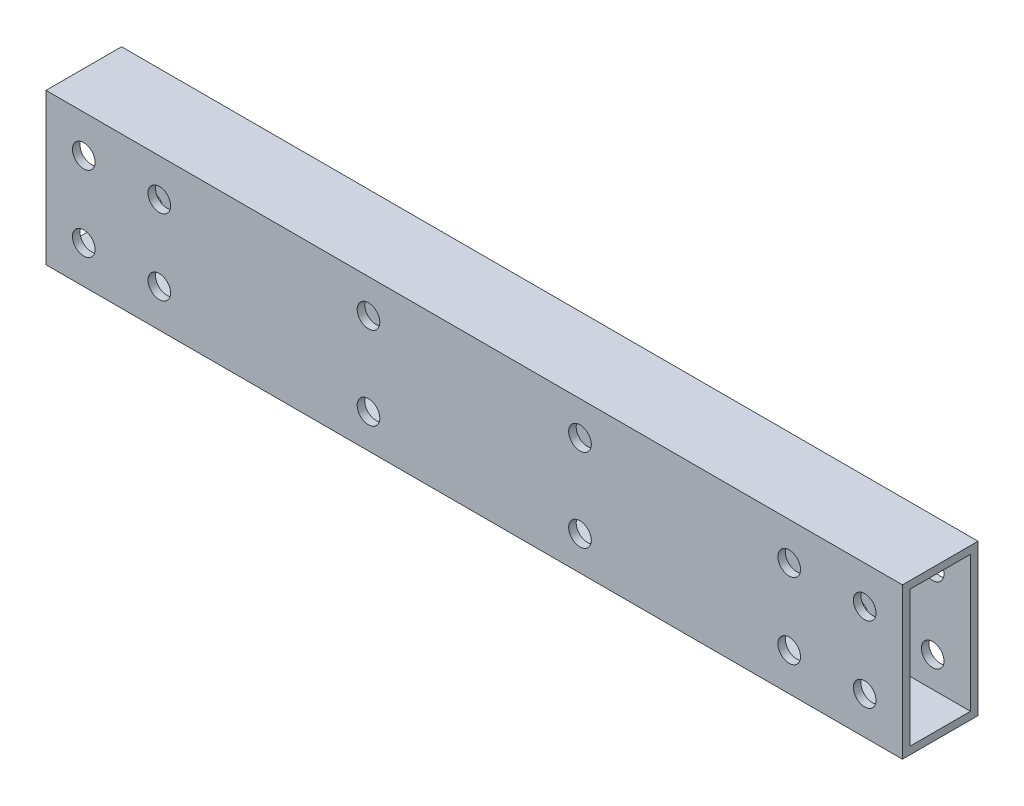
SolidWorks part; units mm, degrees
material "1060 合金"
ref_plane "前视基准面" through (0, 0, 0) normal (0, 0, 1) x (1, 0, 0)
ref_plane "上视基准面" through (0, 0, 0) normal (0, 1, 0) x (1, 0, 0)
ref_plane "右视基准面" through (0, 0, 0) normal (1, 0, 0) x (0, 0, -1)
sketch "草图1" plane through (0, 0, 0) normal (0, 0, 1) x (1, 0, 0)
  line L0 (0, 0) -> (113.4, 0)
  dimension "D1" = 113.4
other "Jiqirendui 20X10X1(1)"
ref_plane "基准面1" through (0, 0, 0) normal (1, 0, 0) x (0, 1, 0)
sketch "草图11" plane through (0, 0, 0) normal (1, 0, 0) x (0, 1, 0)
  line L1 (10, -5) -> (-10, -5)
  line L2 (10, -5) -> (10, 5)
  line L3 (10, 5) -> (-10, 5)
  line L4 (-10, -5) -> (-10, 5)
  line L7 (9, -4) -> (-9, -4)
  line L8 (9, -4) -> (9, 4)
  line L9 (9, 4) -> (-9, 4)
  line L10 (-9, -4) -> (-9, 4)
  point P0 (0, 0)
  point P5 (0, 0)
  point P11 (0, 0)
  dimension "D1" = 10
  dimension "D2" = 8
  dimension "D3" = 20
  dimension "D4" = 18
  dimension "D5" = 1
sketch "草图12" plane through (0, 0, 5) normal (0, 0, 1) x (1, 0, 0)
  line L0 (113.4, 10) -> (0, 10) construction
  line L1 (5, 5) -> (15, 5) construction
  line L2 (5, 5) -> (5, -5) construction
  line L3 (5, -5) -> (15, -5) construction
  line L4 (15, 5) -> (15, -5) construction
  line L5 (5, 5) -> (15, -5) construction
  line L6 (5, -5) -> (15, 5) construction
  line L7 (98.4, 5) -> (108.4, 5) construction
  line L8 (98.4, 5) -> (98.4, -5) construction
  line L9 (98.4, -5) -> (108.4, -5) construction
  line L10 (108.4, 5) -> (108.4, -5) construction
  line L11 (98.4, 5) -> (108.4, -5) construction
  line L12 (98.4, -5) -> (108.4, 5) construction
  line L13 (0, 10) -> (0, -10) construction
  line L14 (113.4, 10) -> (113.4, -10) construction
  circle A0 centre (15, 5) radius 1.5
  circle A1 centre (5, 5) radius 1.5
  circle A2 centre (15, -5) radius 1.5
  circle A3 centre (5, -5) radius 1.5
  circle A4 centre (108.4, -5) radius 1.5
  circle A5 centre (108.4, 5) radius 1.5
  circle A6 centre (98.4, 5) radius 1.5
  circle A7 centre (98.4, -5) radius 1.5
  point P0 (10, 0)
  point P5 (103.4, 0)
  dimension "D7" = 3
  dimension "D8" = 3
  dimension "D9" = 3
  dimension "D10" = 3
  dimension "D11" = 3
  dimension "D12" = 3
  dimension "D13" = 3
  dimension "D14" = 3
  dimension "D1" = 10
  dimension "D2" = 10
  dimension "D3" = 5
  dimension "D4" = 5
  dimension "D5" = 5
  dimension "D6" = 5
extrude "切除-拉伸1" cut sketch "草图12" against normal blind 10
sketch "草图13" plane through (0, 0, 5) normal (0, 0, 1) x (1, 0, 0)
  line L5 (0, 0) -> (113.4, 0) construction
  line L6 (113.4, 10) -> (113.4, -10) construction
  line L8 (56.7, 10) -> (56.7, -10) construction
  line L9 (113.4, 10) -> (0, 10) construction
  line L10 (113.4, -10) -> (0, -10) construction
  line L12 (42.7, -5.5) -> (70.7, -5.5) construction
  line L13 (42.7, -5.5) -> (42.7, 5.5) construction
  line L14 (42.7, 5.5) -> (70.7, 5.5) construction
  line L15 (70.7, -5.5) -> (70.7, 5.5) construction
  line L16 (42.7, -5.5) -> (70.7, 5.5) construction
  line L17 (42.7, 5.5) -> (70.7, -5.5) construction
  circle A6 centre (42.7, 5.5) radius 1.5
  circle A7 centre (70.7, 5.5) radius 1.5
  circle A8 centre (70.7, -5.5) radius 1.5
  circle A9 centre (42.7, -5.5) radius 1.5
  point P10 (56.7, 0)
  dimension "D3" = 3
  dimension "D1" = 28
  dimension "D2" = 11
extrude "切除-拉伸2" cut sketch "草图13" against normal through all
